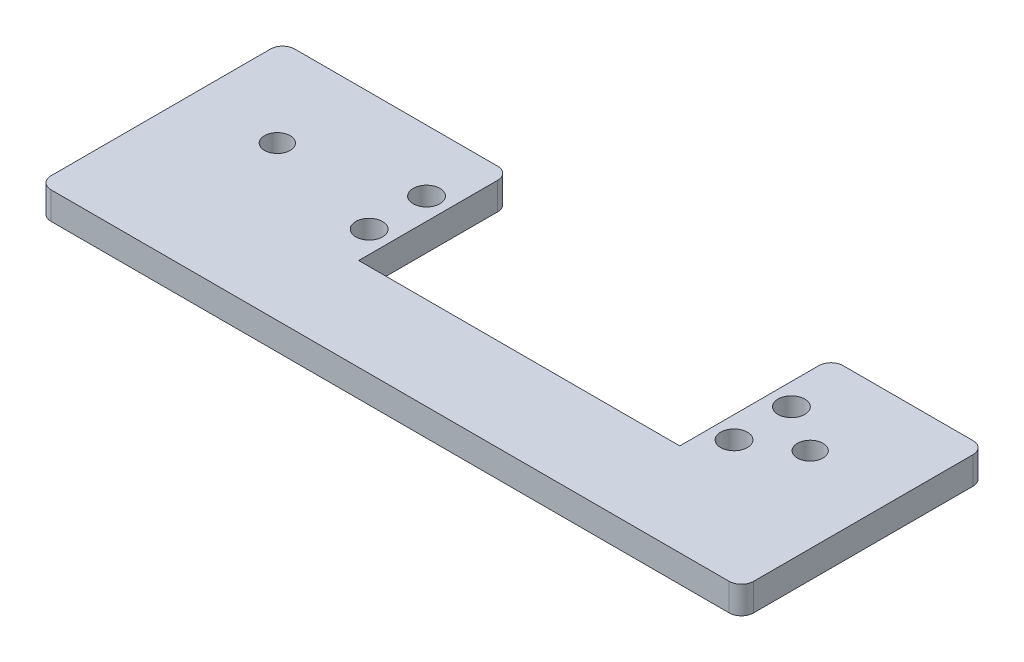
SolidWorks part; units mm, degrees
ref_plane "Front Plane" through (0, 0, 0) normal (0, 0, 1) x (1, 0, 0)
ref_plane "Top Plane" through (0, 0, 0) normal (0, 1, 0) x (1, 0, 0)
ref_plane "Right Plane" through (0, 0, 0) normal (1, 0, 0) x (0, 0, -1)
sketch "Sketch1" plane through (0, 0, 0) normal (0, 1, 0) x (1, 0, 0)
  line L0 (0, 20.039) -> (0, -20.039) construction
  line L1 (55.75, 20.039) -> (34.4017, 20.039)
  line L2 (57.75, 18.039) -> (57.75, -18.039)
  line L3 (55.75, -20.039) -> (-55.75, -20.039)
  line L4 (-57.75, 18.039) -> (-57.75, -18.039)
  line L5 (57.75, 20.039) -> (-57.75, -20.039) construction
  line L6 (57.75, -20.039) -> (-57.75, 20.039) construction
  line L7 (-57.75, 5.219) -> (57.75, 5.219) construction
  line L8 (-20.3883, 18.039) -> (-20.3883, -4.816)
  line L9 (32.4017, 18.039) -> (32.4017, -4.816)
  line L10 (-20.3883, -4.816) -> (32.4017, -4.816)
  line L11 (6.0067, -4.816) -> (6.0067, 20.039) construction
  line L12 (-22.3883, 20.039) -> (-55.75, 20.039)
  circle A0 centre (-43.8023, 5.219) radius 2.1082
  circle A1 centre (43.8023, 5.219) radius 2.1082
  circle A2 centre (-5.3283, 5.219) radius 7.0091 construction
  circle A3 centre (-23.9883, 9.934) radius 2.2
  circle A4 centre (36.0017, 9.934) radius 2.2
  circle A5 centre (36.0017, 0.504) radius 2.2
  circle A6 centre (-23.9883, 0.504) radius 2.2
  arc A7 (-20.3883, 18.039) -> (-22.3883, 20.039) centre (-22.3883, 18.039) ccw
  arc A8 (32.4017, 18.039) -> (34.4017, 20.039) centre (34.4017, 18.039) cw
  arc A9 (55.75, 20.039) -> (57.75, 18.039) centre (55.75, 18.039) cw
  arc A10 (57.75, -18.039) -> (55.75, -20.039) centre (55.75, -18.039) cw
  arc A11 (-55.75, -20.039) -> (-57.75, -18.039) centre (-55.75, -18.039) cw
  arc A12 (-55.75, 20.039) -> (-57.75, 18.039) centre (-55.75, 18.039) ccw
  point P0 (0, 0)
  point P32 (-20.3883, 20.039)
  dimension "D2" = 4.2164
  dimension "D12" = 4.4
  dimension "D13" = 2
  dimension "D1" = 14.82
  dimension "D3" = 43.8023
  dimension "D4" = 115.5
  dimension "D5" = 38.474
  dimension "D6" = 15.06
  dimension "D7" = 37.73
  dimension "D8" = 10.035
  dimension "D9" = 4.715
  dimension "D10" = 40.078
  dimension "D11" = 3.6
extrude "Boss-Extrude1" add sketch "Sketch1" along normal blind 4.5
